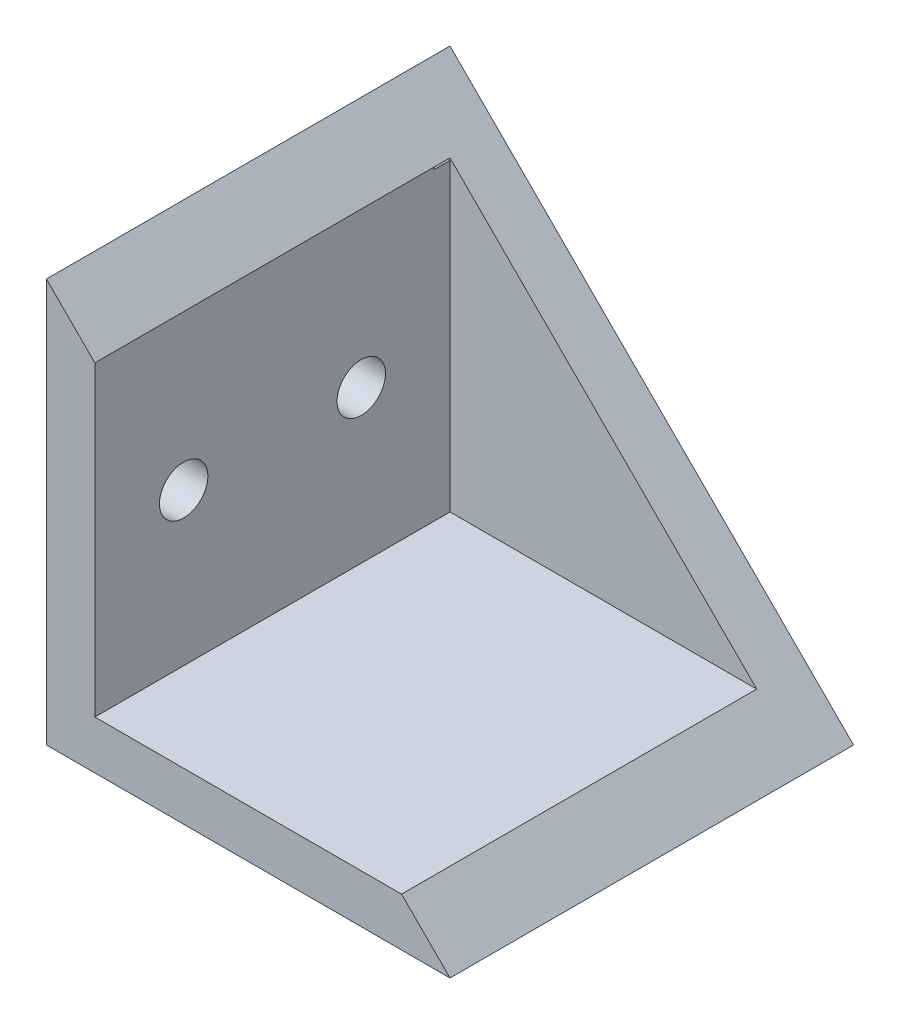
SolidWorks part; units mm, degrees
ref_plane "Front Plane" through (0, 0, 0) normal (0, 0, 1) x (1, 0, 0)
ref_plane "Top Plane" through (0, 0, 0) normal (0, 1, 0) x (1, 0, 0)
ref_plane "Right Plane" through (0, 0, 0) normal (1, 0, 0) x (0, 0, -1)
sketch "Sketch1" plane through (0, 0, 0) normal (0, 0, 1) x (1, 0, 0)
  line L0 (0, 24.3075) -> (0, -0.6925)
  line L1 (0, -0.6925) -> (25, -0.6925)
  line L2 (0, 24.3075) -> (25, -0.6925)
  dimension "D1" = 25
  dimension "D2" = 25
extrude "Boss-Extrude2" add sketch "Sketch1" along normal blind 25
sketch "Sketch2" plane through (0, 0, 25) normal (0, 0, 1) x (1, 0, 0)
  line L0 (3, 21.3075) -> (3, 2.3075)
  line L1 (25, -0.6925) -> (0, 24.3075) construction
  line L2 (3, 2.3075) -> (22, 2.3075)
  line L3 (0, 24.3075) -> (0, -0.6925) construction
  line L4 (0, -0.6925) -> (25, -0.6925) construction
  line L5 (3, 21.3075) -> (22, 2.3075)
  dimension "D1" = 3
  dimension "D2" = 3
extrude "Cut-Extrude1" cut sketch "Sketch2" against normal blind 21
sketch "Sketch3" plane through (12.1537, 12.1537, 0) normal (0.7071, 0.7071, 0) x (0.7071, -0.7071, 0)
  line L0 (-12.9453, -4) -> (13.9247, -4)
  line L4 (13.9247, -4) -> (13.9247, -3)
  line L5 (13.9247, -3) -> (-12.9453, -3)
  line L6 (-12.9453, -3) -> (-12.9453, -4)
extrude "Cut-Extrude3" cut sketch "Sketch3" against normal blind 0.1
sketch "Sketch4" plane through (0, 0, 4) normal (0, 0, 1) x (1, 0, 0)
  line L0 (3, 21.3075) -> (3, 2.3075)
  line L1 (3, 2.3075) -> (22, 2.3075)
  line L2 (22, 2.3075) -> (3, 21.3075)
extrude "Cut-Extrude4" cut sketch "Sketch4" against normal up to surface (1 mm away) up to face at (12.4646, 11.7721, 3)
sketch "Sketch5" plane through (0, 0, 3) normal (0, 0, 1) x (1, 0, 0)
  line L0 (22, 2.3075) -> (21.8586, 2.3075)
  line L1 (21.8586, 2.3075) -> (21.9293, 2.2368)
  line L2 (21.9293, 2.2368) -> (22, 2.3075)
extrude "Boss-Extrude3" add sketch "Sketch5" along normal up to surface (1 mm away) up to face at (21.9293, 2.2839, 4)
sketch "Sketch6" plane through (0, 2.3075, 0) normal (0, 1, 0) x (1, 0, 0)
  line L0 (22, -3) -> (3, -3) construction
  line L1 (3, -3) -> (3, -25) construction
  line L2 (3, -25) -> (22, -25)
sketch "Sketch8" plane through (3, 0, 0) normal (1, 0, 0) x (0, 0, -1)
  line L0 (-25, 2.3075) -> (-25, 21.3075) construction
  line L1 (-25, 21.3075) -> (-3, 21.3075) construction
  line L2 (-25, 21.3075) -> (-14, 21.3075)
  line L3 (-14, 21.3075) -> (-3, 21.3075)
  line L4 (-3, 21.3075) -> (-3, 11.7368)
  line L5 (-3, 21.166) -> (-3, 2.3075) construction
  line L6 (-3, 11.7368) -> (-3, 2.3075)
  circle A0 centre (-8.5, 11.7368) radius 1.5
  circle A1 centre (-19.5, 11.7368) radius 1.5
  dimension "D1" = 3
  dimension "D2" = 3
extrude "Cut-Extrude5" cut sketch "Sketch8" against normal blind 18 and the other way blind 15 contours A0 | A1
